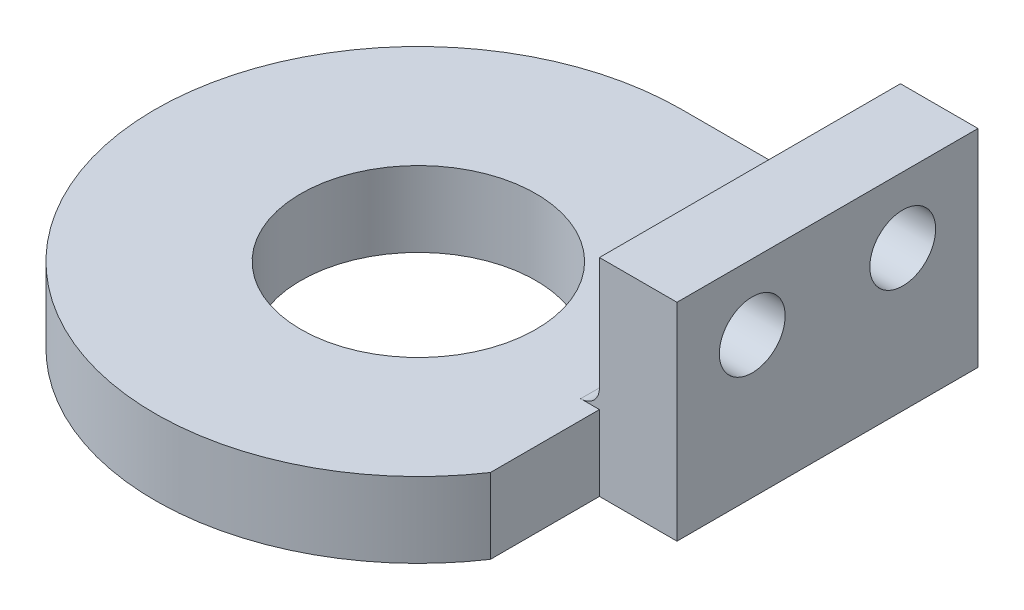
SolidWorks part; units mm, degrees
ref_plane "Front Plane" through (0, 0, 0) normal (0, 0, 1) x (1, 0, 0)
ref_plane "Top Plane" through (0, 0, 0) normal (0, 1, 0) x (1, 0, 0)
ref_plane "Right Plane" through (0, 0, 0) normal (1, 0, 0) x (0, 0, -1)
sketch "Sketch1" plane through (0, 0, 0) normal (0, 1, 0) x (1, 0, 0)
  line L0 (0, 14) -> (15.75, 14)
  line L2 (15.75, 14) -> (15.75, -2.002)
  line L3 (15.75, -2.002) -> (11.6284, -2.002)
  line L4 (11.6284, -2.002) -> (11.6284, -7.7962)
  line L5 (15.75, 14.6777) -> (15.75, 13.1777) construction
  line L6 (15.75, 13.1777) -> (15.75, -2.3223) construction
  circle A0 centre (0, 0) radius 6.25
  circle A1 centre (0, 0) radius 11.25 construction
  arc A2 (0, 14) -> (11.6284, -7.7962) centre (0, 0) ccw
  dimension "D1" = 12.5
  dimension "D2" = 22.5
  dimension "D3" = 14
extrude "Boss-Extrude1" add sketch "Sketch1" along normal blind 4
sketch "Sketch2" plane through (0, 4, 0) normal (0, 1, 0) x (1, 0, 0)
  line L0 (11.6284, -2.002) -> (15.75, -2.002) construction
  line L1 (15.75, 14) -> (11.6284, 14)
  line L2 (15.75, 14) -> (15.75, -2.002)
  line L3 (15.75, -2.002) -> (11.6284, -2.002)
  line L4 (11.6284, 14) -> (11.6284, -2.002)
  line L5 (11.6284, -7.7962) -> (11.6284, -2.002) construction
extrude "Boss-Extrude2" add sketch "Sketch2" along normal blind 7
sketch "Sketch3" plane through (11.6284, 0, 0) normal (-1, 0, 0) x (0, 0, 1)
  line L0 (-14, 7.5) -> (2.002, 7.5) construction
  line L1 (-14, 11) -> (-14, 4) construction
  line L2 (2.002, 11) -> (2.002, 4) construction
  line L3 (-5.999, 11) -> (-5.999, 4) construction
  line L4 (-14, 11) -> (2.002, 11) construction
  line L5 (14, 4) -> (-14, 4) construction
  circle A0 centre (-9.999, 7.5) radius 1.75
  circle A1 centre (-1.999, 7.5) radius 1.75
  dimension "D1" = 8
  dimension "D2" = 4
extrude "Cut-Extrude1" cut sketch "Sketch3" against normal through all contours A1 | A0
fillet "Fillet2" radius 1 1 edges at (11.6284, 4, -5.999)
